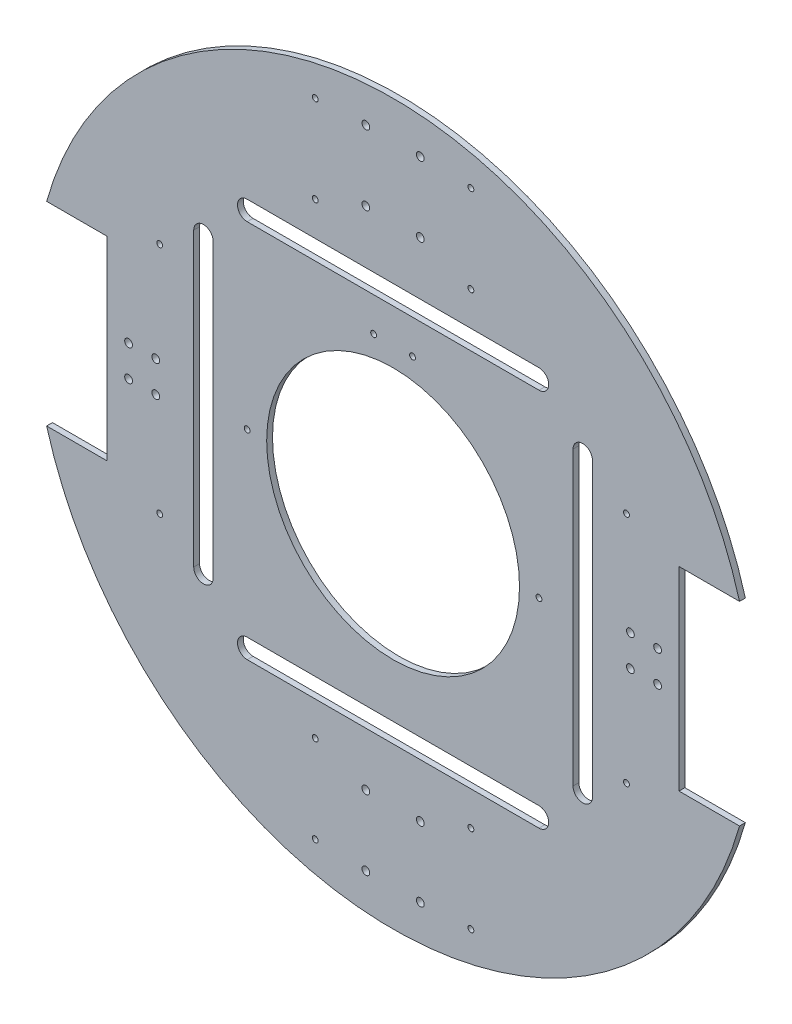
SolidWorks part; units mm, degrees
ref_plane "前视基准面" through (0, 0, 0) normal (0, 0, 1) x (1, 0, 0)
ref_plane "上视基准面" through (0, 0, 0) normal (0, 1, 0) x (1, 0, 0)
ref_plane "右视基准面" through (0, 0, 0) normal (1, 0, 0) x (0, 0, -1)
sketch "草图1" plane through (0, 0, 0) normal (0, 0, 1) x (1, 0, 0)
  line L0 (-439.6733, 0) -> (439.6733, 0) construction
  line L1 (147, 50) -> (178.1151, 50)
  line L2 (147, -50) -> (178.1151, -50)
  line L3 (-147, 30) -> (-147, 0)
  line L4 (147, 30) -> (147, 0)
  line L7 (0, -246.6367) -> (0, 197.8194) construction
  line L8 (-178.1151, 50) -> (-147, 50)
  line L9 (-178.1151, -50) -> (-147, -50)
  line L11 (147, -50) -> (147, 50)
  line L12 (-147, -50) -> (-147, 50)
  line L16 (0, -8) -> (0, 8)
  line L17 (-75, -97.5) -> (75, -97.5) construction
  line L18 (-75, -102.5) -> (75, -102.5)
  line L19 (-97.5, -75) -> (-97.5, 75) construction
  line L20 (-102.5, -75) -> (-102.5, 75)
  line L21 (-92.5, -75) -> (-92.5, 75)
  line L22 (-75, -92.5) -> (75, -92.5)
  line L23 (97.5, -75) -> (97.5, 75) construction
  line L24 (102.5, -75) -> (102.5, 75)
  line L25 (92.5, -75) -> (92.5, 75)
  line L26 (-75, 97.5) -> (75, 97.5) construction
  line L27 (-75, 102.5) -> (75, 102.5)
  line L28 (-75, 92.5) -> (75, 92.5)
  arc A0 (-178.1151, -50) -> (178.1151, -50) centre (0, 0) ccw
  arc A1 (178.1151, 50) -> (-178.1151, 50) centre (0, 0) ccw
  circle A2 centre (-136, 8) radius 2
  circle A3 centre (-122, 8) radius 2
  circle A4 centre (-122, -8) radius 2
  circle A5 centre (-136, -8) radius 2
  circle A6 centre (122, 8) radius 2
  circle A7 centre (136, 8) radius 2
  circle A8 centre (136, -8) radius 2
  circle A9 centre (122, -8) radius 2
  circle A10 centre (14, 166) radius 2
  circle A11 centre (14, 130) radius 2
  circle A12 centre (-14, 130) radius 2
  circle A13 centre (-14, 166) radius 2
  circle A14 centre (-14, -166) radius 2
  circle A15 centre (-14, -130) radius 2
  circle A16 centre (14, -130) radius 2
  circle A17 centre (14, -166) radius 2
  circle A18 centre (-40, 165) radius 1.5
  circle A19 centre (40, 165) radius 1.5
  circle A20 centre (40, -120) radius 1.5
  circle A21 centre (-40, -120) radius 1.5
  circle A22 centre (-40, 120) radius 1.5
  circle A23 centre (40, 120) radius 1.5
  circle A24 centre (-40, -165) radius 1.5
  circle A25 centre (40, -165) radius 1.5
  circle A26 centre (-120, 60) radius 1.5
  circle A27 centre (-120, -60) radius 1.5
  circle A28 centre (120, -60) radius 1.5
  circle A29 centre (120, 60) radius 1.5
  circle A30 centre (0, 0) radius 65
  arc A31 (-102.5, -75) -> (-92.5, -75) centre (-97.5, -75) ccw
  arc A32 (-92.5, 75) -> (-102.5, 75) centre (-97.5, 75) ccw
  arc A33 (-75, -102.5) -> (-75, -92.5) centre (-75, -97.5) cw
  arc A34 (75, -92.5) -> (75, -102.5) centre (75, -97.5) cw
  arc A35 (102.5, -75) -> (92.5, -75) centre (97.5, -75) cw
  arc A36 (92.5, 75) -> (102.5, 75) centre (97.5, 75) cw
  arc A37 (-75, 102.5) -> (-75, 92.5) centre (-75, 97.5) ccw
  arc A38 (75, 92.5) -> (75, 102.5) centre (75, 97.5) ccw
  circle A39 centre (-75, 0) radius 1.5
  circle A40 centre (75, 0) radius 1.5
  circle A41 centre (-10, 75) radius 1.5
  circle A42 centre (10, 75) radius 1.5
  point P5 (-147, 0)
  point P10 (0, 0)
  point P13 (0, -24.4087)
  point P16 (0, 50)
  point P19 (0, -50)
  point P20 (147, 0)
  point P21 (0, 130)
  point P22 (0, 0)
  point P25 (147, 0)
  point P28 (-147, 0)
  point P34 (0, 0)
  point P35 (0, 0)
  point P55 (0, 130)
  point P59 (0, 175)
  point P68 (0, 0)
  point P73 (0, 165)
  point P79 (0, -120)
  point P91 (-120, 0)
  point P97 (-97.5, 0)
  point P100 (0, 0)
  point P103 (0, 97.5)
  point P108 (0, -97.5)
  point P115 (97.5, 0)
  point P126 (0, 166)
  point P132 (0, 75)
  dimension "D1" = 8
  dimension "D2" = 50
  dimension "D3" = 60
  dimension "D4" = 97.5
  dimension "D7" = 36
  dimension "D5" = 120
  dimension "D13" = 5
  dimension "D14" = 3
  dimension "D15" = 130
  dimension "D19" = 185
  dimension "D20" = 4
  dimension "D21" = 75
  dimension "D6" = 130
  dimension "D8" = 45
  dimension "D9" = 28
  dimension "D10" = 80
  dimension "D11" = 75
  dimension "D12" = 75
  dimension "D16" = 120
  dimension "D17" = 122
  dimension "D18" = 14
  dimension "D22" = 10
  dimension "D23" = 30
extrude "凸台-拉伸5" add sketch "草图1" along normal blind 3 contours L1 A1 L8 L12 L3 L9 A0 L2 L11 L4 A38 L28 A37 L27 A32 L21 A31 L20 A30 A28 A27 A26 A24 A22 A21 A20 A19 A18 A16 A14 A13 A12
sketch "草图2" plane through (0, 0, 3) normal (0, 0, 1) x (1, 0, 0)
sketch "草图3" plane through (0, 0, 3) normal (0, 0, 1) x (1, 0, 0)
